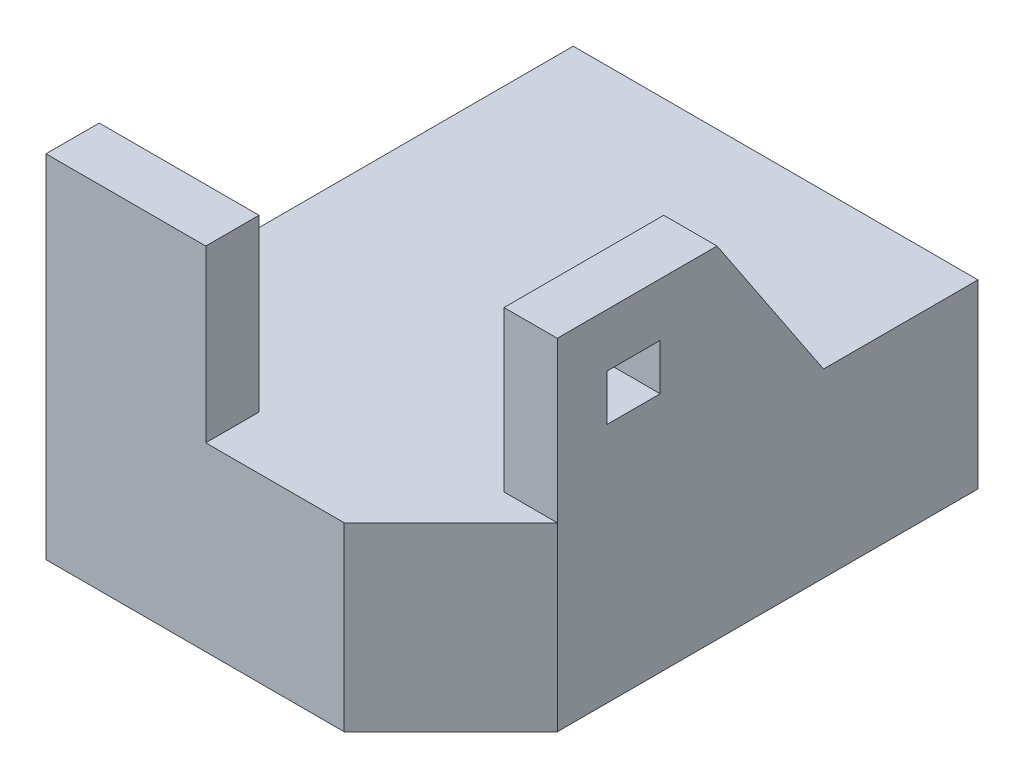
SolidWorks part; units mm, degrees
ref_plane "Front Plane" through (0, 0, 0) normal (0, 0, 1) x (1, 0, 0)
ref_plane "Top Plane" through (0, 0, 0) normal (0, 1, 0) x (1, 0, 0)
ref_plane "Right Plane" through (0, 0, 0) normal (1, 0, 0) x (0, 0, -1)
sketch "Sketch1" plane through (0, 0, 0) normal (0, 1, 0) x (1, 0, 0)
  line L0 (0, 0) -> (0, -2514.6)
  line L1 (0, -2514.6) -> (1422.4, -2514.6)
  line L2 (1422.4, -2514.6) -> (1930.4, -2006.6)
  line L3 (0, 0) -> (1930.4, 0)
  line L4 (1930.4, 0) -> (1930.4, -2006.6)
  point P3 (854.2144, -2514.6)
  dimension "D1" = 2514.6
  dimension "D2" = 1930.4
  dimension "D3" = 508
  dimension "D4" = 45
other "AlignGroup1"
extrude "Boss-Extrude1" add sketch "Sketch1" along normal blind 863.6 contours L0 L1 L2 L4 L3
sketch "Sketch4" plane through (0, 863.6, 0) normal (0, 1, 0) x (1, 0, 0)
  line L2 (762, -2260.6) -> (0, -2260.6)
  line L3 (762, -2260.6) -> (762, -2514.6)
  line L4 (762, -2514.6) -> (0, -2514.6)
  line L5 (0, -2260.6) -> (0, -2514.6)
  dimension "D1" = 762
  dimension "D2" = 254
extrude "Boss-Extrude2" add sketch "Sketch4" along normal blind 812.8
sketch "Sketch8" plane through (1930.4, 0, 0) normal (1, 0, 0) x (0, 0, -1)
  line L0 (-2006.6, 863.6) -> (-736.6, 863.6)
  line L1 (0, 863.6) -> (-2006.6, 863.6) construction
  line L2 (-736.6, 863.6) -> (-1244.6, 1625.6)
  line L3 (-1244.6, 1625.6) -> (-2006.6, 1625.6)
  line L4 (-2006.6, 1625.6) -> (-2006.6, 863.6)
  line L6 (-1769.7861, 1371.6) -> (-1515.7861, 1371.6)
  line L7 (-1769.7861, 1371.6) -> (-1769.7861, 1150.9335)
  line L8 (-1769.7861, 1150.9335) -> (-1515.7861, 1150.9335)
  line L9 (-1515.7861, 1371.6) -> (-1515.7861, 1150.9335)
  point P11 (-2006.6, 863.6)
  point P12 (0, 0)
  dimension "D1" = 762
  dimension "D2" = 1270
  dimension "D3" = 762
  dimension "D4" = 254
  dimension "D5" = 254
extrude "Boss-Extrude4" add sketch "Sketch8" against normal blind 254
